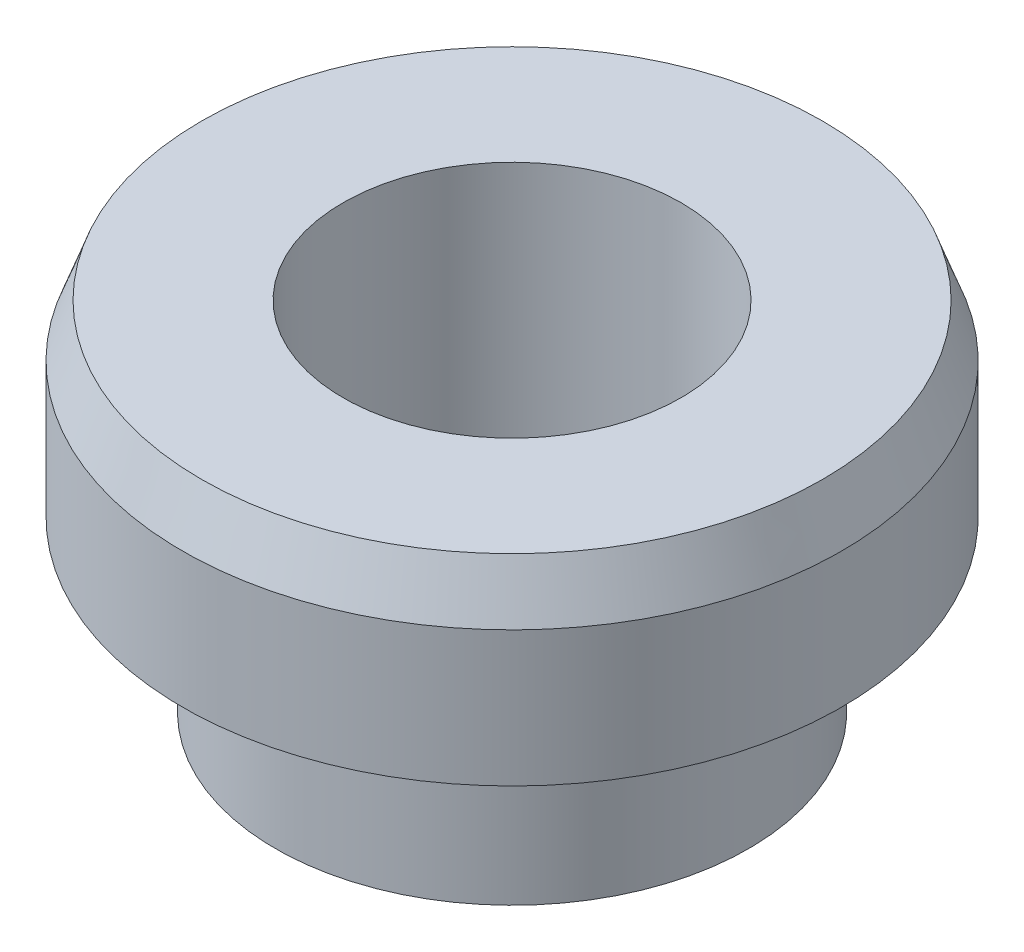
SolidWorks part; units mm, degrees
ref_plane "Front Plane" through (0, 0, 0) normal (0, 0, 1) x (1, 0, 0)
ref_plane "Top Plane" through (0, 0, 0) normal (0, 1, 0) x (1, 0, 0)
ref_plane "Right Plane" through (0, 0, 0) normal (1, 0, 0) x (0, 0, -1)
sketch "Sketch1" plane through (0, 0, 0) normal (0, 0, 1) x (1, 0, 0)
  line L0 (0, 0) -> (0, 5.4195) construction
  line L3 (9.75, 8.9092) -> (9.75, 4.9092)
  line L4 (9.75, 4.9092) -> (7, 4.9092)
  line L5 (7, 4.9092) -> (7, -0.0908)
  line L6 (7, -0.0908) -> (5, -0.0908)
  line L7 (5, -0.0908) -> (5, 10.4618)
  line L8 (5, 10.4618) -> (9.1849, 10.4618)
  line L10 (9.1849, 10.4618) -> (9.75, 8.9092)
  point P11 (7.8207, 6.4237)
  point P12 (7.1124, 7.8733)
  point P13 (5, -0.0908)
  point P14 (5, -0.1426)
  point P15 (5, -0.0303)
  dimension "D1" = 14
  dimension "D3" = 110
  dimension "D4" = 5
  dimension "D5" = 19.5
  dimension "D6" = 4
revolve "Revolve1" add sketch "Sketch1" angle 360 about L0
